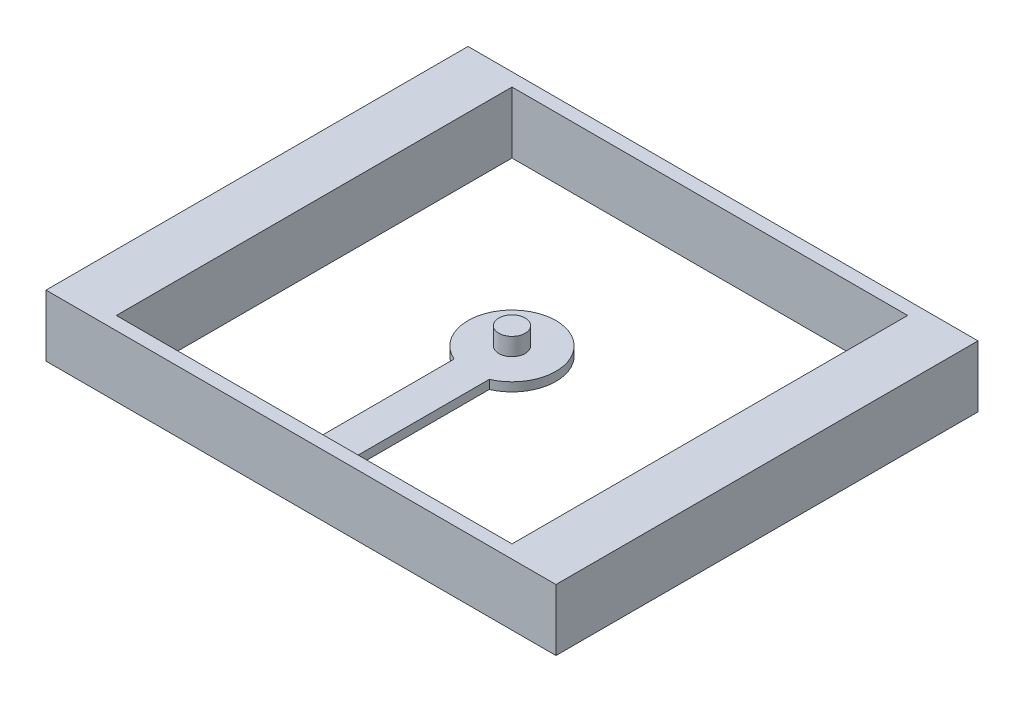
SolidWorks part; units mm, degrees
ref_plane "Front Plane" through (0, 0, 0) normal (0, 0, 1) x (1, 0, 0)
ref_plane "Top Plane" through (0, 0, 0) normal (0, 1, 0) x (1, 0, 0)
ref_plane "Right Plane" through (0, 0, 0) normal (1, 0, 0) x (0, 0, -1)
sketch "Sketch1" plane through (0, 0, 0) normal (0, 0, 1) x (1, 0, 0)
  line L1 (0, 0) -> (58, 0)
  line L2 (0, 0) -> (0, -7)
  line L3 (0, -7) -> (58, -7)
  line L4 (58, 0) -> (58, -7)
  dimension "D1" = 58
  dimension "D2" = 7
extrude "Boss-Extrude1" add sketch "Sketch1" along normal blind 48
sketch "Sketch2" plane through (0, 0, 0) normal (0, 1, 0) x (1, 0, 0)
  line L0 (0, 0) -> (58, -48)
  line L2 (6.5, -1.5) -> (51.5, -1.5)
  line L3 (6.5, -1.5) -> (6.5, -46.5)
  line L4 (6.5, -46.5) -> (51.5, -46.5)
  line L5 (51.5, -1.5) -> (51.5, -46.5)
  line L6 (6.5, -1.5) -> (51.5, -46.5) construction
  line L7 (6.5, -46.5) -> (51.5, -1.5) construction
  point P4 (29, -24)
  dimension "D1" = 45
  dimension "D2" = 45
extrude "Cut-Extrude1" cut sketch "Sketch2" against normal blind 3 contours L5 L0 L3 L4 | L5 L2 L3 L0
sketch "Sketch4" plane through (0, -7, 0) normal (0, -1, 0) x (1, 0, 0)
  line L0 (0, 48) -> (58, 0)
  line L1 (58, 48) -> (0, 0)
  line L3 (6.5, 46.5) -> (51.5, 46.5)
  line L4 (6.5, 46.5) -> (6.5, 1.5)
  line L5 (6.5, 1.5) -> (51.5, 1.5)
  line L6 (51.5, 46.5) -> (51.5, 1.5)
  line L7 (6.5, 46.5) -> (51.5, 1.5) construction
  line L8 (6.5, 1.5) -> (51.5, 46.5) construction
  point P8 (29, 24)
  dimension "D1" = 45
  dimension "D2" = 45
extrude "Cut-Extrude2" cut sketch "Sketch4" against normal blind 3 contours L6 L0 L1 L4 L5 | L6 L1 L0 | L6 L3 L4 L0 L1 | L0 L4 L1
sketch "Sketch5" plane through (0, -3, 0) normal (0, 1, 0) x (1, 0, 0)
  line L0 (6.5, -1.5) -> (51.5, -46.5)
  line L1 (29, -24) -> (29, -46.5)
  line L2 (6.5, -46.5) -> (51.5, -46.5) construction
  line L3 (27, -46.5) -> (31, -46.5)
  line L4 (6.5, -46.5) -> (51.5, -46.5) construction
  line L5 (27, -46.5) -> (27, -28.5826)
  line L6 (31, -46.5) -> (31, -28.5826)
  circle A0 centre (29, -24) radius 5
  point P14 (29, -46.5)
  line M3 (51.5, -46.5) -> (51.5, -1.5)
  line M4 (51.5, -1.5) -> (6.5, -1.5)
  line M5 (6.5, -1.5) -> (6.5, -46.5)
  line M6 (6.5, -46.5) -> (51.5, -46.5)
  dimension "D1" = 10
  dimension "D2" = 4
extrude "Cut-Extrude3" cut sketch "Sketch5" against normal blind 3 contours A0 L0 L5 M5 M6 | A0 L0 M3 M4 | A0 L6 L0 M6
sketch "Sketch6" plane through (0, -3, 0) normal (0, 1, 0) x (1, 0, 0)
  circle A0 centre (29, -24) radius 1.5
  dimension "D1" = 3
extrude "Boss-Extrude2" add sketch "Sketch6" along normal blind 2
